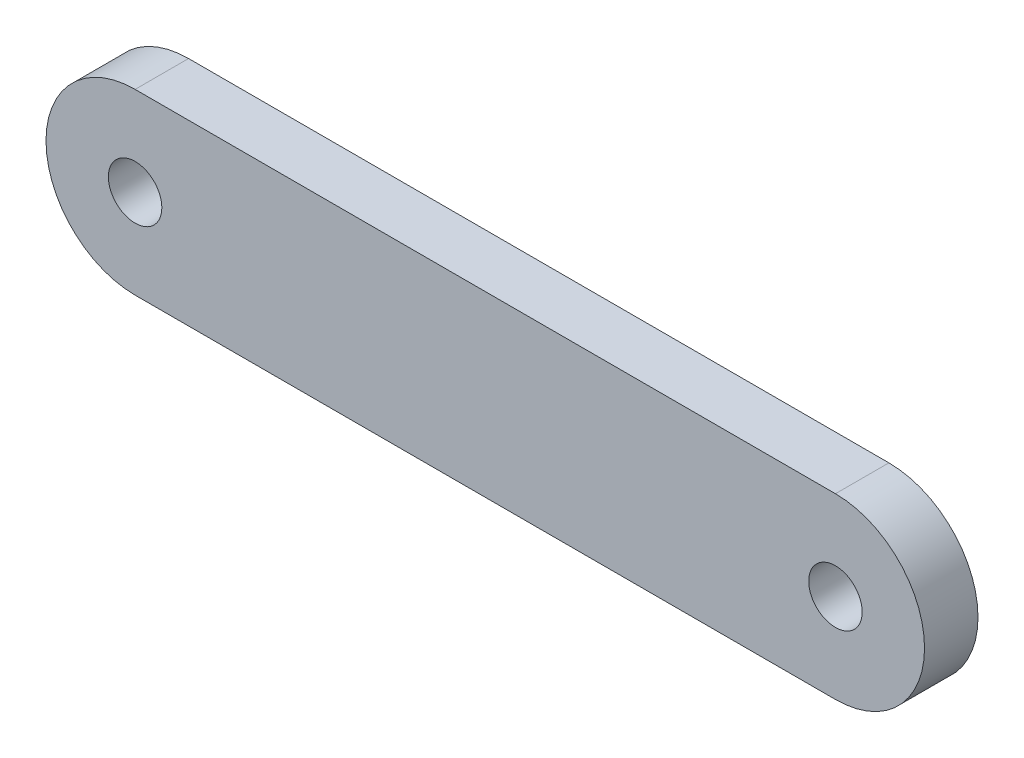
SolidWorks part; units mm, degrees
material "Acrylic (Medium-high impact)"
ref_plane "Front Plane" through (0, 0, 0) normal (0, 0, 1) x (1, 0, 0)
ref_plane "Top Plane" through (0, 0, 0) normal (0, 1, 0) x (1, 0, 0)
ref_plane "Right Plane" through (0, 0, 0) normal (1, 0, 0) x (0, 0, -1)
sketch "Sketch1" plane through (0, 0, 0) normal (0, 0, 1) x (1, 0, 0)
  line L0 (0, 0) -> (39.3, 0) construction
  line L1 (0, 5) -> (39.3, 5)
  line L2 (0, -5) -> (39.3, -5)
  arc A0 (0, 5) -> (0, -5) centre (0, 0) ccw
  arc A1 (39.3, -5) -> (39.3, 5) centre (39.3, 0) ccw
  circle A2 centre (0, 0) radius 1.5
  circle A3 centre (39.3, 0) radius 1.5
  point P3 (19.65, 0)
  dimension "D3" = 3
  dimension "D4" = 3
  dimension "D1" = 39.3
  dimension "D2" = 10
extrude "Boss-Extrude1" add sketch "Sketch1" along normal blind 3
